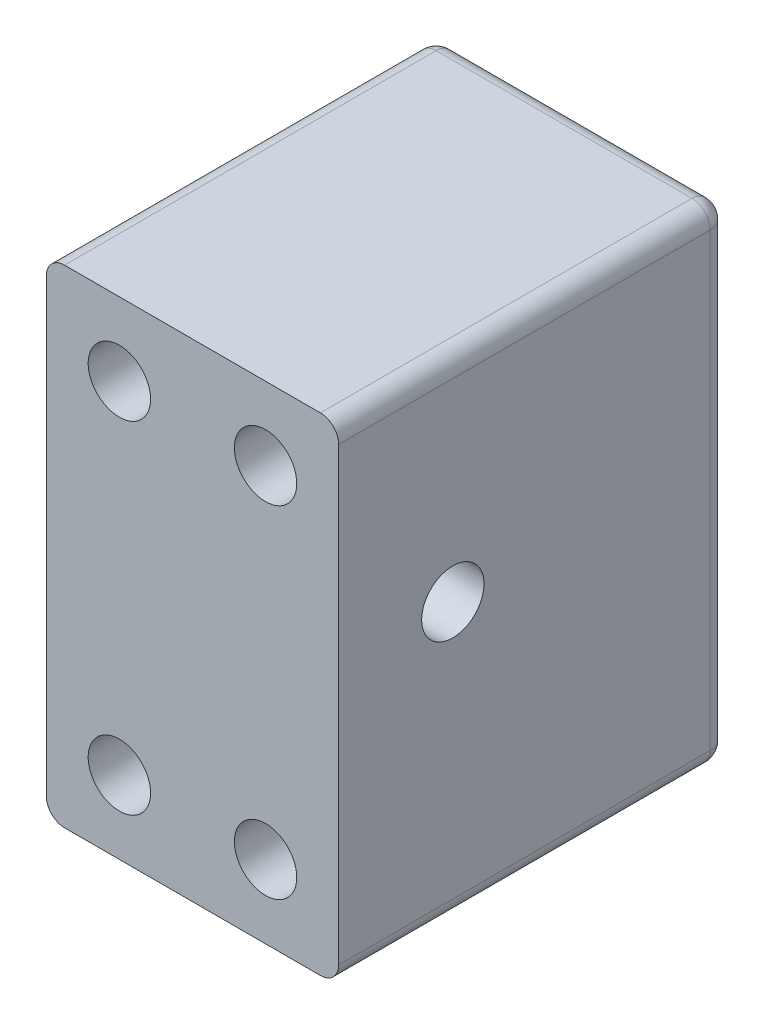
SolidWorks part; units mm, degrees
ref_plane "Front Plane" through (0, 0, 0) normal (0, 0, 1) x (1, 0, 0)
ref_plane "Top Plane" through (0, 0, 0) normal (0, 1, 0) x (1, 0, 0)
ref_plane "Right Plane" through (0, 0, 0) normal (1, 0, 0) x (0, 0, -1)
sketch "Sketch1" plane through (0, 0, 0) normal (0, 0, 1) x (1, 0, 0)
  line L0 (0, 26.9875) -> (19.05, 26.9875) construction
  line L1 (0, 0) -> (19.05, 0)
  line L2 (0, 0) -> (0, 31.75)
  line L3 (0, 31.75) -> (19.05, 31.75)
  line L4 (19.05, 0) -> (19.05, 31.75)
  circle A0 centre (4.7625, 26.9875) radius 2.032
  circle A1 centre (14.2875, 26.9875) radius 2.032
  circle A2 centre (4.7625, 4.7625) radius 2.032
  circle A3 centre (14.2875, 4.7625) radius 2.032
  point P14 (9.525, 31.75)
  dimension "D3" = 4.064
  dimension "D1" = 31.75
  dimension "D2" = 19.05
  dimension "D5" = 4.7625
  dimension "D6" = 4.7625
  dimension "D7" = 4.7625
  dimension "D4" = 4.7625
extrude "Boss-Extrude1" add sketch "Sketch1" along normal blind 25.4
sketch "Sketch2" plane through (0, 0, 0) normal (-1, 0, 0) x (0, 0, 1)
  line L4 (0, 0) -> (17.9605, 17.9605) construction
  line L5 (25.4, 0) -> (0, 0) construction
  circle A4 centre (17.9605, 17.9605) radius 2.032
  point P6 (0, 0)
  dimension "D2" = 25.4
  dimension "D3" = 4.064
  dimension "D1" = 45
extrude "Cut-Extrude1" cut sketch "Sketch2" against normal through all
fillet "Fillet1" radius 1.1906 8 edges at (9.525, 0, 0) (9.525, 31.75, 0) (19.05, 15.875, 0) (0, 15.875, 0) (0, 0, 12.7) (19.05, 0, 12.7) (0, 31.75, 12.7) (19.05, 31.75, 12.7)
equation "\"D4@Sketch1\"=\"D7@Sketch1\""
